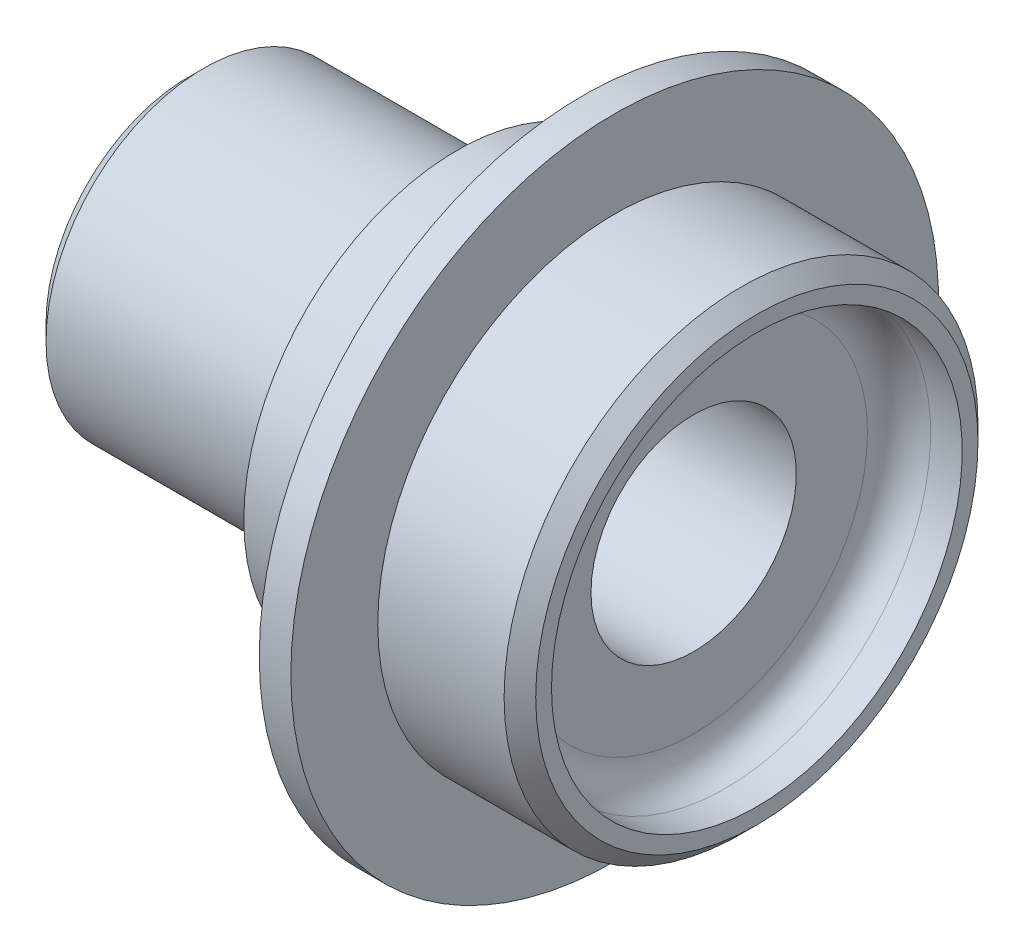
SolidWorks part; units mm, degrees
ref_plane "Front Plane" through (0, 0, 0) normal (0, 0, 1) x (1, 0, 0)
ref_plane "Top Plane" through (0, 0, 0) normal (0, 1, 0) x (1, 0, 0)
ref_plane "Right Plane" through (0, 0, 0) normal (1, 0, 0) x (0, 0, -1)
sketch "Sketch2" plane through (0, 0, 0) normal (0, 0, 1) x (1, 0, 0)
  line L0 (0, 0) -> (36, 0) construction
  line L1 (0, 8) -> (0, 10)
  line L2 (0, 10) -> (15, 10)
  line L3 (15, 10) -> (17.0207, 13.5)
  line L4 (17.0207, 13.5) -> (25, 13.5)
  line L5 (25, 13.5) -> (25, 20.5)
  line L6 (25, 20.5) -> (27, 20.5)
  line L7 (27, 20.5) -> (27, 15)
  line L8 (27, 15) -> (36, 15)
  line L9 (36, 15) -> (36, 13)
  line L10 (36, 13) -> (34, 13)
  line L11 (32, 11) -> (32, 6.5)
  line L12 (32, 6.5) -> (12, 6.5)
  line L13 (12, 6.5) -> (12, 5.5)
  line L14 (12, 5.5) -> (10, 5.5)
  line L15 (10, 5.5) -> (10, 8)
  line L16 (10, 8) -> (0, 8)
  arc A0 (34, 13) -> (32, 11) centre (34, 11) ccw
  point P5 (20.7493, 6.5)
  point P20 (0, 0)
  point P21 (17.1946, 13.5)
  point P24 (32, 13)
  dimension "D18" = 2
  dimension "D1" = 36
  dimension "D2" = 8
  dimension "D3" = 10
  dimension "D4" = 20.5
  dimension "D5" = 15
  dimension "D6" = 13
  dimension "D7" = 6.5
  dimension "D8" = 5.5
  dimension "D9" = 13.5
  dimension "D10" = 10
  dimension "D11" = 20
  dimension "D12" = 4
  dimension "D13" = 36
  dimension "D14" = 9
  dimension "D15" = 15
  dimension "D16" = 10
  dimension "D17" = 120
revolve "Revolve1" add sketch "Sketch2" angle 360 about L0
chamfer "Chamfer1" distance 1 angle 45 2 edges at (0, 0, 10) (36, 0, 15)
